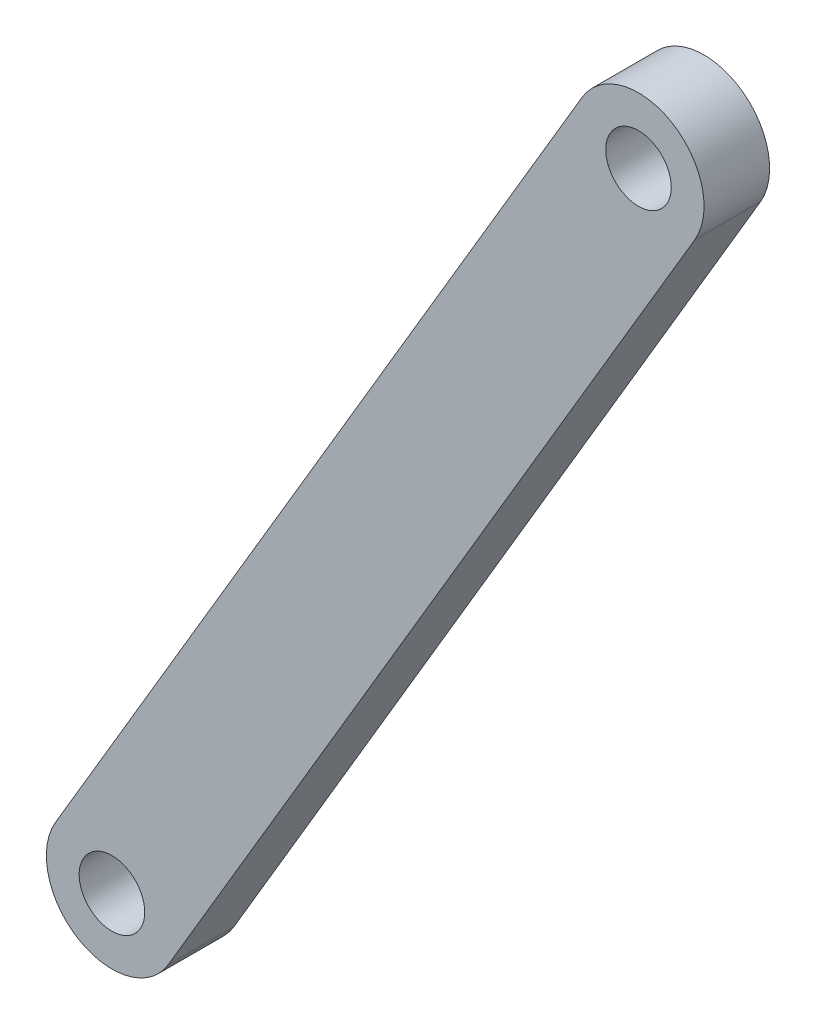
SolidWorks part; units mm, degrees
ref_plane "Front Plane" through (0, 0, 0) normal (0, 0, 1) x (1, 0, 0)
ref_plane "Top Plane" through (0, 0, 0) normal (0, 1, 0) x (1, 0, 0)
ref_plane "Right Plane" through (0, 0, 0) normal (1, 0, 0) x (0, 0, -1)
sketch "Sketch1" plane through (0, 0, 0) normal (0, 0, 1) x (1, 0, 0)
  line L0 (0, 0) -> (304.8, 0) construction
  line L1 (-12.7, -279.4) -> (101.3988, -86.3097) construction
  line L2 (0, 0) -> (0, -279.4) construction
  line L8 (0, -279.4) -> (-12.7, -279.4) construction
  line L9 (101.3988, -86.3097) -> (152.4, 0) construction
  line L10 (95.9319, -83.0792) -> (146.9331, 3.2304)
  line L11 (106.8657, -89.5401) -> (157.8669, -3.2304)
  arc A0 (95.9319, -83.0792) -> (106.8657, -89.5401) centre (101.3988, -86.3097) ccw
  arc A1 (157.8669, -3.2304) -> (146.9331, 3.2304) centre (152.4, 0) ccw
  circle A2 centre (152.4, 0) radius 3.175
  circle A3 centre (101.3988, -86.3097) radius 3.175
  point P3 (126.8994, -43.1548)
  point P15 (132.4213, -176.674)
  point P16 (132.4213, -176.674)
  point P17 (78.5909, -126.826)
  dimension "D5" = 6.35
  dimension "D3" = 12.7
  dimension "D4" = 12.7
  dimension "D1" = 304.8
  dimension "D2" = 279.4
  dimension "D6" = 224.282
extrude "Boss-Extrude1" add sketch "Sketch1" along normal blind 6.35
